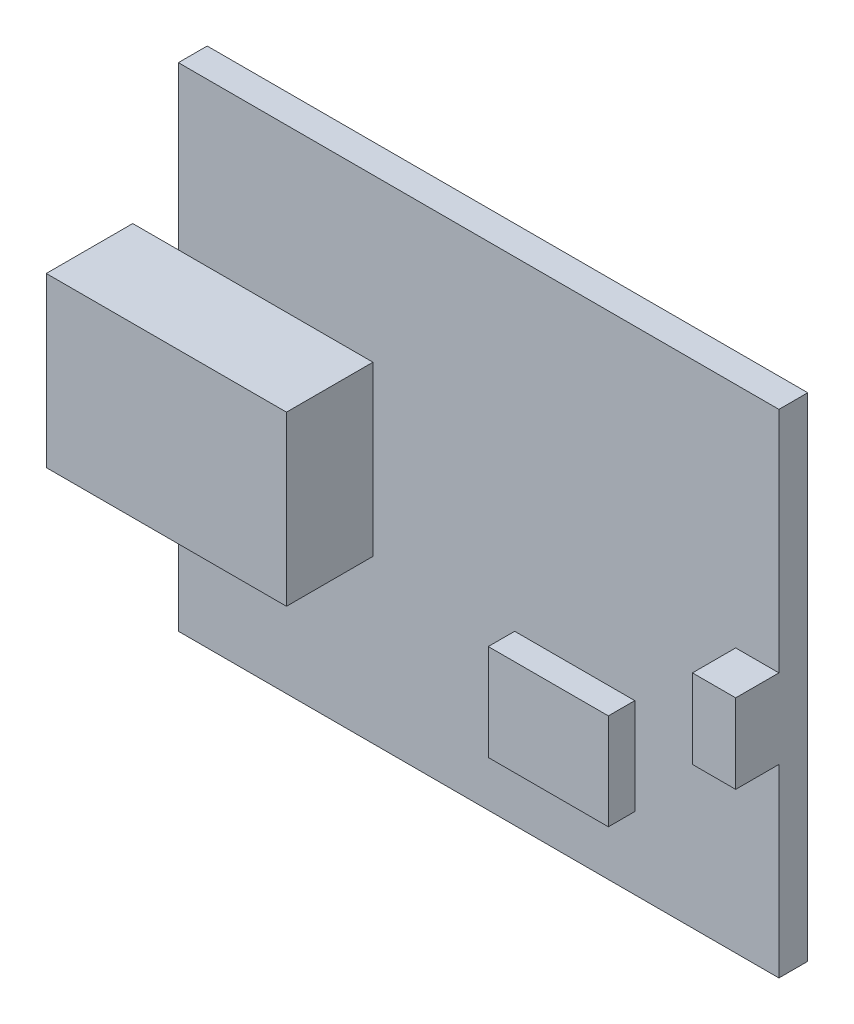
SolidWorks part; units mm, degrees
ref_plane "Front Plane" through (0, 0, 0) normal (0, 0, 1) x (1, 0, 0)
ref_plane "Top Plane" through (0, 0, 0) normal (0, 1, 0) x (1, 0, 0)
ref_plane "Right Plane" through (0, 0, 0) normal (1, 0, 0) x (0, 0, -1)
sketch "Sketch1" plane through (0, 0, 0) normal (0, 0, 1) x (1, 0, 0)
  line L0 (-12.5, 10.25) -> (12.5, -10.25) construction
  line L1 (-12.5, -10.25) -> (12.5, -10.25)
  line L2 (-12.5, -10.25) -> (-12.5, 10.25)
  line L3 (-12.5, 10.25) -> (12.5, 10.25)
  line L4 (12.5, -10.25) -> (12.5, 10.25)
  point P5 (0, 0)
  dimension "D1" = 25
  dimension "D2" = 20.5
extrude "Boss-Extrude1" add sketch "Sketch1" along normal blind 1.2
sketch "Sketch2" plane through (-12.5, 0, 0) normal (-1, 0, 0) x (0, 0, 1)
  line L0 (1.2, 10.25) -> (1.2, -10.25) construction
  line L1 (1.2, 3.5) -> (4.8, 3.5)
  line L2 (1.2, 3.5) -> (1.2, -3.5)
  line L3 (1.2, -3.5) -> (4.8, -3.5)
  line L4 (4.8, 3.5) -> (4.8, -3.5)
  line L5 (0, 0) -> (4.7935, 0) construction
  line L6 (0, 10.25) -> (0, -10.25) construction
  point P7 (4.8, 0)
  dimension "D1" = 7
  dimension "D2" = 3.6
extrude "USB Connector" add sketch "Sketch2" against normal blind 10 from offset 1.9
sketch "Sketch3" plane through (0, 0, 1.2) normal (0, 0, 1) x (1, 0, 0)
  line L0 (10.7, 0.75) -> (12.5, 0.75)
  line L1 (10.7, 0.75) -> (10.7, -2.55)
  line L2 (12.5, 0.75) -> (12.5, -2.55)
  line L3 (10.7, -2.55) -> (12.5, -2.55)
  line L6 (12.5, -10.25) -> (12.5, 10.25) construction
  line L7 (-12.5, -10.25) -> (12.5, -10.25) construction
  dimension "D1" = 3.3
  dimension "D2" = 1.8
  dimension "D3" = 11
extrude "MicroProcessor" add sketch "Sketch3" along normal blind 1.8
sketch "Sketch4" plane through (0, 0, 1.2) normal (0, 0, 1) x (1, 0, 0)
  line L1 (1.5, -3.25) -> (6.5, -3.25)
  line L2 (1.5, -3.25) -> (1.5, -7.25)
  line L3 (1.5, -7.25) -> (6.5, -7.25)
  line L4 (6.5, -3.25) -> (6.5, -7.25)
  line L5 (12.5, -10.25) -> (12.5, -2.55) construction
  line L6 (-12.5, -10.25) -> (12.5, -10.25) construction
  dimension "D1" = 4
  dimension "D2" = 5
  dimension "D3" = 11
  dimension "D4" = 7
extrude "Button Base" add sketch "Sketch4" along normal blind 1.1
sketch "Sketch5" plane through (0, 0, 2.3) normal (0, 0, 1) x (1, 0, 0)
  line L0 (1.5, -3.25) -> (6.5, -7.25) construction
  circle A0 centre (4, -5.25) radius 0.6136
